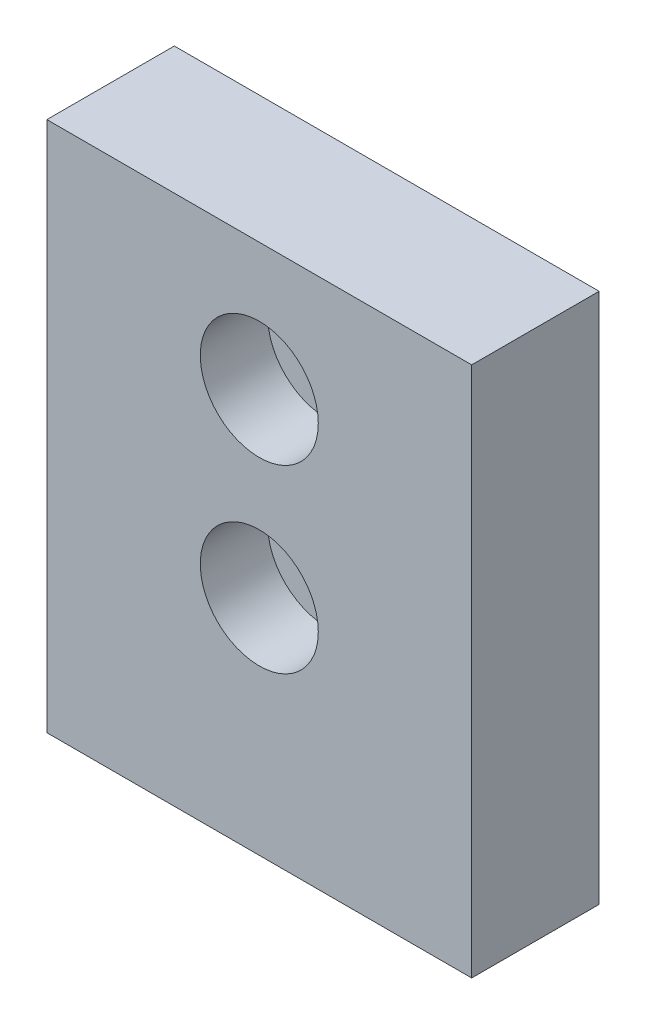
SolidWorks part; units mm, degrees
material "6061-T6 (SS)"
ref_plane "Front Plane" through (0, 0, 0) normal (0, 0, 1) x (1, 0, 0)
ref_plane "Top Plane" through (0, 0, 0) normal (0, 1, 0) x (1, 0, 0)
ref_plane "Right Plane" through (0, 0, 0) normal (1, 0, 0) x (0, 0, -1)
sketch "Sketch1" plane through (0, 0, 0) normal (0, 0, 1) x (1, 0, 0)
  line L0 (20, 0) -> (-20, 0)
  line L1 (-20, 0) -> (-20, 50)
  line L2 (20, 0) -> (20, 50)
  line L3 (-20, 50) -> (20, 50)
  point P4 (0, 0)
  dimension "D1" = 50
  dimension "D2" = 40
extrude "Boss-Extrude1" add sketch "Sketch1" along normal blind 12
hole_wizard "CBORE for 1/4 Socket Head Cap Screw1" positions "Sketch2" profile "Sketch4" counterbore size "1/4" standard "ANSI Inch" end condition through all
sketch "Sketch2" plane through (0, 0, 12) normal (0, 0, 1) x (1, 0, 0)
  line L0 (0, 38) -> (0, 50) construction
  line L1 (20, 50) -> (-20, 50) construction
  line L3 (0, 21) -> (0, 38) construction
  point P0 (0, 38)
  point P2 (0, 21)
  dimension "D1" = 12
  dimension "D2" = 17
sketch "Sketch4" plane through (0, 38, 12) normal (1, 0, 0) x (0, -1, 0)
  line L0 (0, 0) -> (0, 12)
  line L1 (0, 12) -> (3.3782, 12)
  line L3 (3.3782, 12) -> (3.3782, 6.35)
  line L4 (3.3782, 6.35) -> (5.5562, 6.35)
  line L5 (5.5562, 6.35) -> (5.5563, 0)
  line L7 (5.5563, 0) -> (0, 0)
  line L11 (0, -6.35) -> (0, 107.95) construction
  dimension "Thru Hole Dia." = 6.7564
  dimension "Thru Hole Depth" = 12
  dimension "C'Bore Dia." = 11.1125
  dimension "C'Bore Depth" = 6.35
hole_wizard "#8-32 Tapped Hole1" positions "Sketch5" profile "Sketch6" tap size "#8-32" standard "ANSI Inch"
sketch "Sketch5" plane through (0, 0, 0) normal (0, -1, 0) x (-1, 0, 0)
  line L8 (20, 0) -> (-20, 0)
  line L9 (-20, 0) -> (-20, -12)
  line L10 (-20, -12) -> (20, -12)
  line L11 (20, -12) -> (20, 0)
  line L12 (20, 0) -> (-20, 0)
  line L13 (-20, 0) -> (-20, -12)
  line L14 (-20, -12) -> (20, -12)
  line L15 (20, -12) -> (20, 0)
  line L16 (20, -6) -> (14, -6) construction
  line L18 (-20, -6) -> (-14, -6) construction
  line L32 (-14, -6) -> (14, -6) construction
  point P0 (14, -6)
  point P4 (-14, -6)
  point P46 (0, -6)
  dimension "D2" = 28
  dimension "D1" = 0
cosmetic thread "Hole Thread1" parameters "D1"=8.3333, "D2"=4.1656
cosmetic thread "Hole Thread3" parameters "D1"=8.3333, "D2"=4.1656
sketch "Sketch6" plane through (-14, 0, 6) normal (1, 0, 0) x (0, 0, -1)
  line L0 (0, 0) -> (0, 13.7378)
  line L1 (0, 13.7378) -> (1.7272, 12.7)
  line L2 (1.7272, 12.7) -> (1.7272, 0)
  line L5 (1.7272, 0) -> (0, 0)
  line L10 (0, 13.7378) -> (-1.7272, 12.7) construction
  line L11 (0, -6.35) -> (0, 107.95) construction
  dimension "Tap Drill Dia." = 3.4544
  dimension "Tap Drill Depth" = 12.7
  dimension "Drill Angle" = 118
cosmetic thread "Hole Thread4" parameters "D1"=8.3333, "D2"=4.1656
